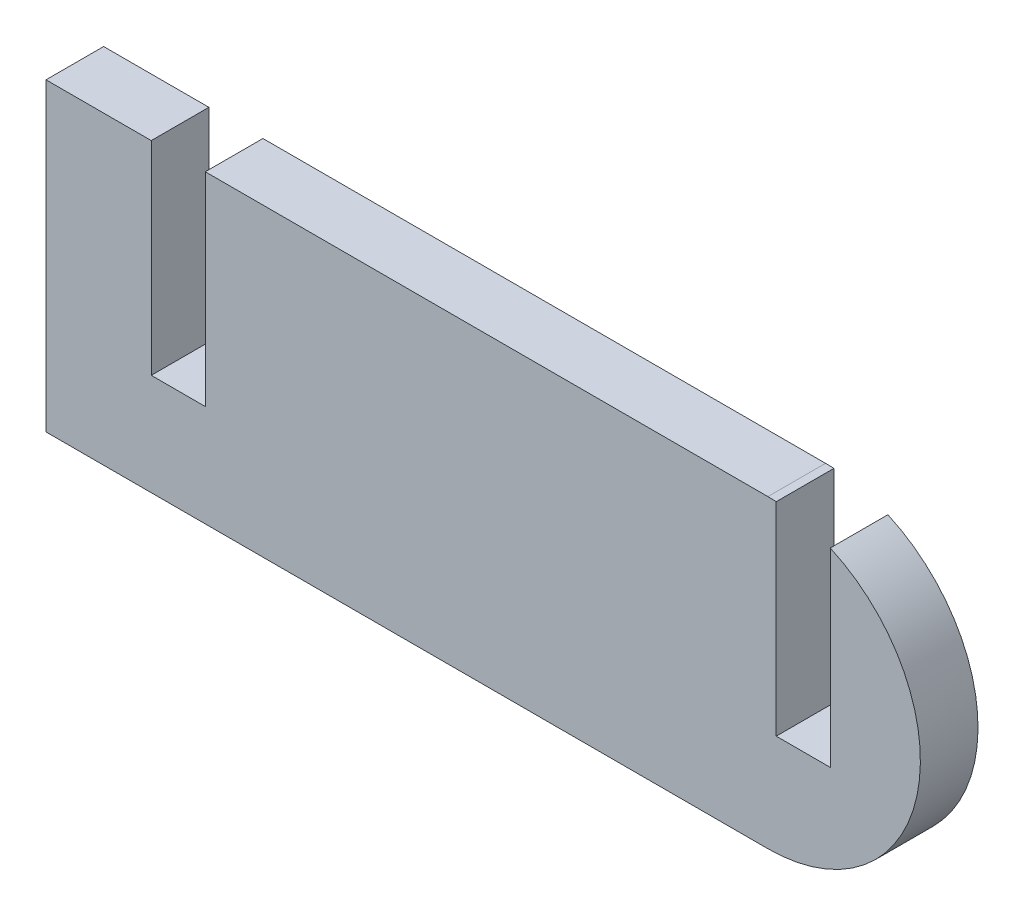
SolidWorks part; units mm, degrees
ref_plane "Front Plane" through (0, 0, 0) normal (0, 0, 1) x (1, 0, 0)
ref_plane "Top Plane" through (0, 0, 0) normal (0, 1, 0) x (1, 0, 0)
ref_plane "Right Plane" through (0, 0, 0) normal (1, 0, 0) x (0, 0, -1)
sketch "Sketch1" plane through (0, 0, 0) normal (0, 0, 1) x (1, 0, 0)
  line L1 (-88.7437, -110.1994) -> (-12.5437, -110.1994)
  line L2 (-88.7437, -110.1994) -> (-88.7437, -84.7994)
  line L3 (-88.7437, -84.7994) -> (-12.5437, -84.7994)
  line L4 (-12.5437, -110.1994) -> (-12.5437, -84.7994)
  line L5 (-88.7437, -110.1994) -> (-12.5437, -84.7994) construction
  line L6 (-88.7437, -84.7994) -> (-12.5437, -110.1994) construction
  point P4 (-50.6437, -97.4994)
  dimension "D1" = 25.4
extrude "Boss-Extrude1" add sketch "Sketch1" along normal blind 4.8
sketch "Sketch2" plane through (0, 0, 4.8) normal (0, 0, 1) x (1, 0, 0)
  line L0 (-12.5437, -84.7994) -> (-22.7037, -84.7994) construction
  line L1 (-12.5437, -110.1994) -> (-12.5437, -84.7994) construction
  line L2 (-12.5437, -84.7994) -> (-88.7437, -84.7994) construction
  line L3 (-22.7037, -84.7994) -> (-27.2037, -84.7994)
  line L4 (-22.7037, -84.7994) -> (-22.7037, -101.7327)
  line L5 (-22.7037, -101.7327) -> (-27.2037, -101.7327)
  line L6 (-27.2037, -84.7994) -> (-27.2037, -101.7327)
  line L7 (-22.7037, -84.7994) -> (-27.2037, -101.7327) construction
  line L8 (-22.7037, -101.7327) -> (-27.2037, -84.7994) construction
  point P7 (-24.9537, -93.2661)
  dimension "D1" = 0
  dimension "D2" = 4.5
  dimension "D3" = 10.16
  dimension "D4" = 16.9333
ref_plane "Plane1" through (0, -97.4994, 0) normal (0, -1, 0) x (-1, 0, 0)
sketch "Sketch6" plane through (0, 0, 4.8) normal (0, 0, 1) x (1, 0, 0)
  line L0 (-12.5437, -110.1994) -> (-12.5437, -84.7994) construction
  line L1 (-12.5437, -84.7994) -> (-22.7037, -84.7994) construction
  line L2 (-88.7437, -110.1994) -> (-12.5437, -110.1994) construction
  line L3 (-22.7037, -84.7994) -> (-27.2037, -84.7994) construction
  line L5 (-27.8977, -110.1994) -> (-12.5437, -110.1994)
  line L6 (-12.5437, -110.1994) -> (-12.5437, -84.7994)
  line L7 (-12.5437, -84.7994) -> (-27.8977, -84.7994)
  arc A0 (-27.8977, -110.1994) -> (-27.8977, -84.7994) centre (-27.8977, -97.4994) ccw
  point P0 (-27.8977, -97.4994)
  dimension "D1" = 15.354
  dimension "D2" = 12.7
extrude "Cut-Extrude2" cut sketch "Sketch6" against normal through all
extrude "Cut-Extrude3" cut sketch "Sketch2" against normal through all
sketch "Sketch7" plane through (0, 0, 0) normal (0, 0, -1) x (-1, 0, 0)
  line L0 (27.8977, -84.7994) -> (88.7437, -84.7994) construction
  line L1 (79.2537, -101.7327) -> (74.7537, -101.7327)
  line L2 (79.2537, -101.7327) -> (79.2537, -84.7994)
  line L3 (79.2537, -84.7994) -> (74.7537, -84.7994)
  line L4 (74.7537, -101.7327) -> (74.7537, -84.7994)
  line L5 (79.2537, -101.7327) -> (74.7537, -84.7994) construction
  line L6 (79.2537, -84.7994) -> (74.7537, -101.7327) construction
  line L7 (27.2037, -84.8184) -> (27.2037, -101.7327) construction
  point P4 (77.0037, -93.2661)
  dimension "D2" = 4.5
  dimension "D1" = 16.9333
  dimension "D3" = 0
  dimension "D4" = 47.55
extrude "Cut-Extrude4" cut sketch "Sketch7" against normal through all
sketch "Sketch8" plane through (0, 0, 0) normal (0, 0, -1) x (-1, 0, 0)
  line L2 (79.2537, -86.6992) -> (81.9704, -86.6992)
  line L3 (79.2537, -101.7327) -> (79.2537, -84.7994) construction
  line L4 (88.0204, -109.5994) -> (88.0204, -134.9994) construction
  line L5 (88.7437, -84.7994) -> (88.0204, -84.7994)
  line L6 (88.7437, -84.7994) -> (88.7437, -110.1994)
  line L7 (88.7437, -110.1994) -> (88.0204, -110.1994)
  line L8 (88.0204, -84.7994) -> (88.0204, -110.1994)
  line L9 (88.7437, -84.7994) -> (88.0204, -110.1994) construction
  line L10 (88.7437, -110.1994) -> (88.0204, -84.7994) construction
  line L11 (88.7437, -110.1994) -> (27.8977, -110.1994) construction
  point P8 (88.3821, -97.4994)
  line M14 (27.8977, -110.1994) -> (88.7437, -110.1994)
  line M15 (88.7437, -110.1994) -> (88.7437, -84.7994)
  line M16 (88.7437, -84.7994) -> (79.2537, -84.7994)
extrude "Cut-Extrude5" cut sketch "Sketch8" against normal through all contours L8 M16 M14 M15
sketch "Sketch9" plane through (0, 0, 4.8) normal (0, 0, 1) x (1, 0, 0)
  arc A0 (-27.8977, -110.1994) -> (-22.7037, -85.9101) centre (-27.8977, -97.4994) ccw construction
  point P0 (-15.1977, -97.4994)
equation "\"MDF\"= 4.8mm"
equation "\"Foamcore\"= 4.6mm"
equation "\"PCB\" = 1.6mm"
equation "\"GMaterial\"= \"MDF\""
equation "\"D1@Boss-Extrude1\"=\"GMaterial\""
equation "\"D2@Sketch2\"=\"GMaterial\"-\"TensionOffSet\""
equation "\"D1@Sketch6\"=\"GMaterial\"/2 + .51"
equation "\"SkidLength\" = 1in"
equation "\"D1@Sketch1\"=\"SkidLength\""
equation "\"D1@Sketch7\"=2/3"
equation "\"D2@Sketch7\"=\"GMaterial\"-\"TensionOffSet\""
equation "\"BaseWidth\" = 10in"
equation "\"SkidClearance\" = 0.4in"
equation "\"D4@Sketch7\"=\"MotorMountHeight\" - 2*\"GMaterial\""
equation "\"MotorMountLength\" = 2in"
equation "\"MotorMountWidth\" = \"GMaterial\""
equation "\"MotorMountHeight\" = 2.25in"
equation "\"D1@Sketch4\"=\"SkidClearance\""
equation "\"UnoStackWidth\" = 77.4mm"
equation "\"UnoStackLength\" = 79.8mm"
equation "\"UnoStackHeight\" = 34.2mm"
equation "\"TallHexRiserHeight\" = 22.2mm"
equation "\"PingPongBallSize\" = 40mm"
equation "\"BarrelLength\" = 9in"
equation "\"BarrelSize\" = \"PingPongBallSize\""
equation "\"PlatformLength\" = 4in"
equation "\"PlatformWidth\" = 6in"
equation "\"WheelWidth\"= 26mm"
equation "\"WheelDiameter\"=2.99213"
equation "\"ServoMountHeight\"=2.49223"
equation "\"ServoGearHeight\" = 0.95330261in"
equation "\"ServoMountLength\"= 1.53774"
equation "\"PivotHoleRadius\"= 0.616358"
equation "\"PlatformMountHeight\" = 3.19"
equation "\"TensionOffSet\"= .3mm"
